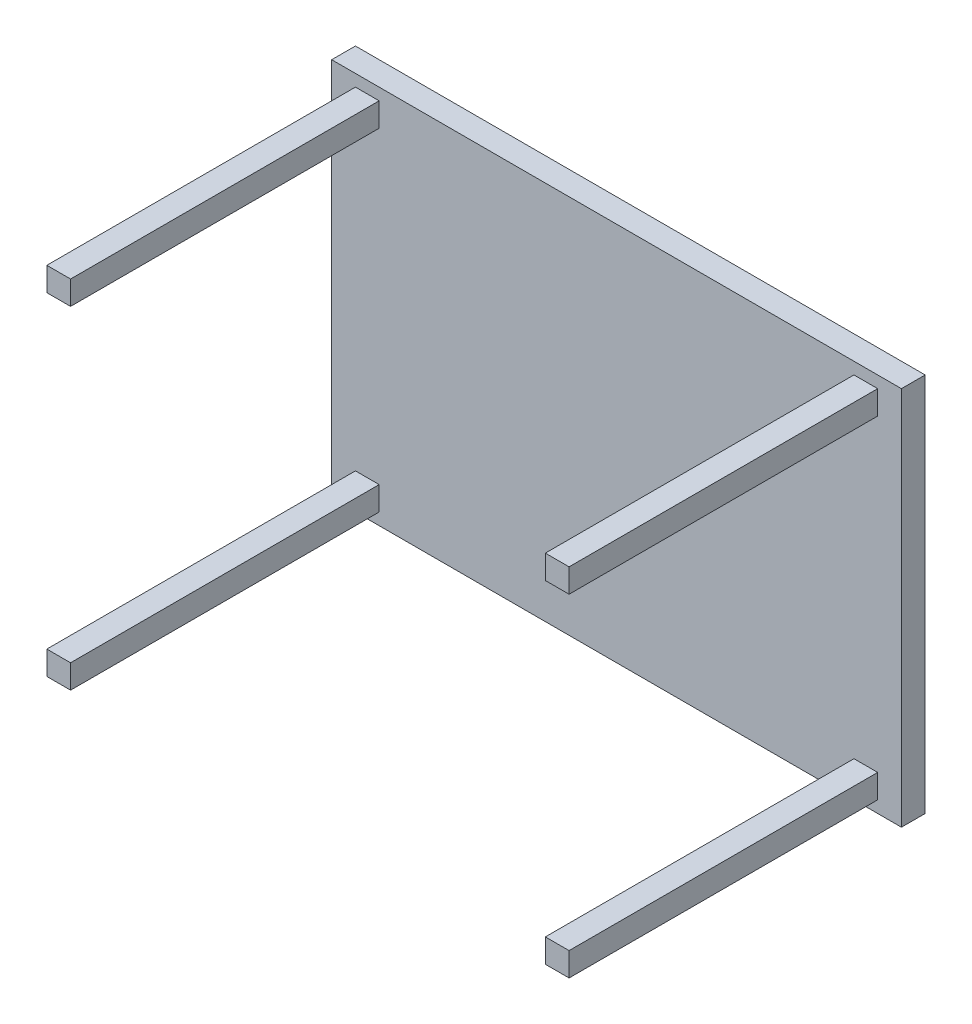
SolidWorks part; units mm, degrees
ref_plane "前视基准面" through (0, 0, 0) normal (0, 0, 1) x (1, 0, 0)
ref_plane "上视基准面" through (0, 0, 0) normal (0, 1, 0) x (1, 0, 0)
ref_plane "右视基准面" through (0, 0, 0) normal (1, 0, 0) x (0, 0, -1)
other "Configuration Table"
sketch "草图1" plane through (0, 0, 0) normal (0, 0, 1) x (1, 0, 0)
  line L1 (-600, -400) -> (600, -400)
  line L2 (-600, -400) -> (-600, 400)
  line L3 (-600, 400) -> (600, 400)
  line L4 (600, -400) -> (600, 400)
  line L5 (-600, -400) -> (600, 400) construction
  line L6 (-600, 400) -> (600, -400) construction
  point P0 (0, 0)
extrude "凸台-拉伸1" add sketch "草图1" along normal blind 50
sketch "草图2" plane through (0, 0, 0) normal (0, 0, 1) x (1, 0, 0)
  line L1 (500, 325) -> (550, 325)
  line L2 (500, 325) -> (500, 375)
  line L3 (500, 375) -> (550, 375)
  line L4 (550, 325) -> (550, 375)
  line L5 (500, 325) -> (550, 375) construction
  line L6 (500, 375) -> (550, 325) construction
  point P0 (525, 350)
extrude "凸台-拉伸2" add sketch "草图2" along normal blind 700
sketch "草图3" plane through (0, 0, 0) normal (0, 0, 1) x (1, 0, 0)
  line L1 (500, -375) -> (550, -375)
  line L2 (500, -375) -> (500, -325)
  line L3 (500, -325) -> (550, -325)
  line L4 (550, -375) -> (550, -325)
  line L5 (500, -375) -> (550, -325) construction
  line L6 (500, -325) -> (550, -375) construction
  point P0 (525, -350)
extrude "凸台-拉伸3" add sketch "草图3" along normal blind 700
sketch "草图4" plane through (0, 0, 0) normal (0, 0, 1) x (1, 0, 0)
  line L1 (-550, 325) -> (-500, 325)
  line L2 (-550, 325) -> (-550, 375)
  line L3 (-550, 375) -> (-500, 375)
  line L4 (-500, 325) -> (-500, 375)
  line L5 (-550, 325) -> (-500, 375) construction
  line L6 (-550, 375) -> (-500, 325) construction
  point P0 (-525, 350)
extrude "凸台-拉伸4" add sketch "草图4" along normal blind 700
sketch "草图5" plane through (0, 0, 0) normal (0, 0, 1) x (1, 0, 0)
  line L1 (-550, -375) -> (-500, -375)
  line L2 (-550, -375) -> (-550, -325)
  line L3 (-550, -325) -> (-500, -325)
  line L4 (-500, -375) -> (-500, -325)
  line L5 (-550, -375) -> (-500, -325) construction
  line L6 (-550, -325) -> (-500, -375) construction
  point P0 (-525, -350)
extrude "凸台-拉伸5" add sketch "草图5" along normal blind 700
sketch "草图6" plane through (0, 0, 0) normal (0, 0, 1) x (1, 0, 0)
  circle A0 centre (0, 0) radius 200
extrude "切除-拉伸1" cut sketch "草图6" along normal blind 20
